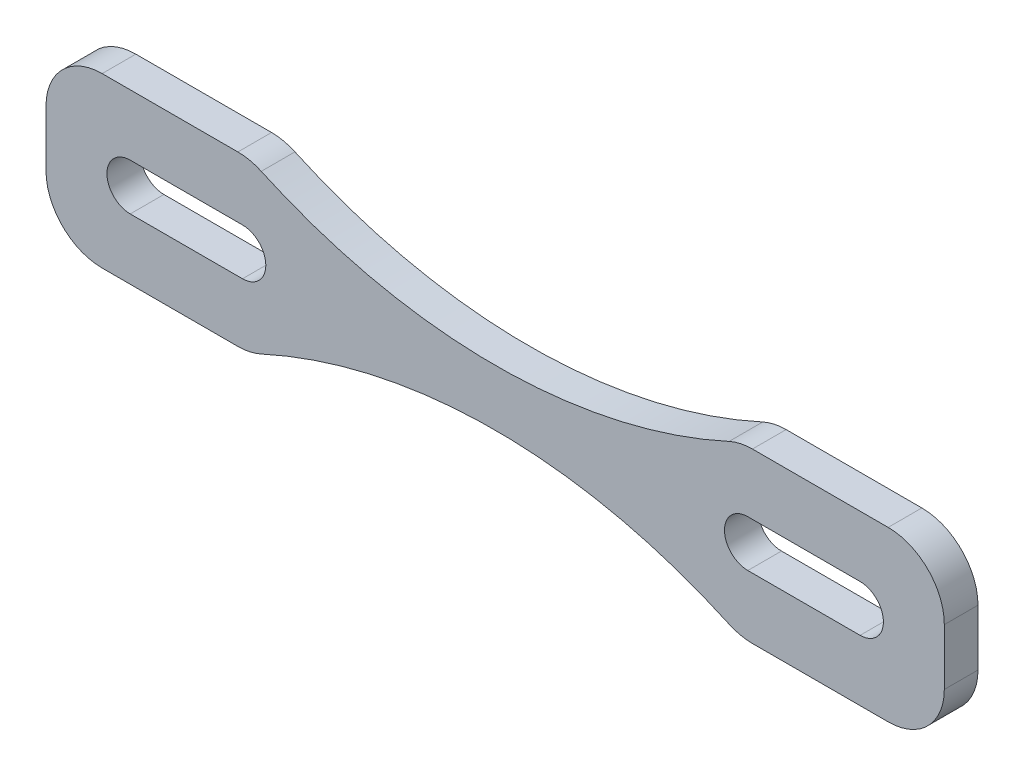
SolidWorks part; units mm, degrees
material "Aluminium 6060 T6"
ref_plane "Front Plane" through (0, 0, 0) normal (0, 0, 1) x (1, 0, 0)
ref_plane "Top Plane" through (0, 0, 0) normal (0, 1, 0) x (1, 0, 0)
ref_plane "Right Plane" through (0, 0, 0) normal (1, 0, 0) x (0, 0, -1)
sketch "Sketch1" plane through (0, 0, 0) normal (0, 0, 1) x (1, 0, 0)
  line L0 (0, 60.754) -> (0, -53.8058) construction
  line L1 (-80, -15) -> (-43.589, -15)
  line L2 (-80, -15) -> (-80, 15)
  line L3 (-80, 15) -> (-43.589, 15)
  line L4 (80, -15) -> (80, 15)
  line L5 (-80, -15) -> (80, 15) construction
  line L6 (-80, 15) -> (80, -15) construction
  line L7 (-65, 0) -> (-45, 0) construction
  line L8 (-65, 4.15) -> (-45, 4.15)
  line L9 (-65, -4.15) -> (-45, -4.15)
  line L10 (65, 0) -> (45, 0) construction
  line L11 (65, 4.15) -> (45, 4.15)
  line L12 (65, -4.15) -> (45, -4.15)
  line L13 (-102.7388, 0) -> (151.9347, 0) construction
  line L14 (43.589, -15) -> (80, -15)
  line L15 (43.589, 15) -> (80, 15)
  arc A2 (-65, 4.15) -> (-65, -4.15) centre (-65, 0) ccw
  arc A3 (-45, -4.15) -> (-45, 4.15) centre (-45, 0) ccw
  arc A4 (65, 4.15) -> (65, -4.15) centre (65, 0) cw
  arc A5 (45, -4.15) -> (45, 4.15) centre (45, 0) cw
  arc A6 (-43.589, 15) -> (43.589, 15) centre (0, 105) ccw
  arc A7 (-43.589, -15) -> (43.589, -15) centre (0, -105) cw
  point P0 (0, 0)
  point P11 (-80, 0)
  point P12 (-55, 0)
  point P19 (55, 0)
  dimension "D2" = 8.3
  dimension "D3" = 20
  dimension "D5" = 10
  dimension "D6" = 100
  dimension "D1" = 30
  dimension "D4" = 110
  dimension "D7" = 160
extrude "Boss-Extrude1" add sketch "Sketch1" along normal blind 6
fillet "Fillet1" radius 10 8 edges at (80, 15, 3) (80, -15, 3) (43.589, -15, 3) (-43.589, -15, 3) (-80, -15, 3) (-80, 15, 3) (43.589, 15, 3) (-43.589, 15, 3)
